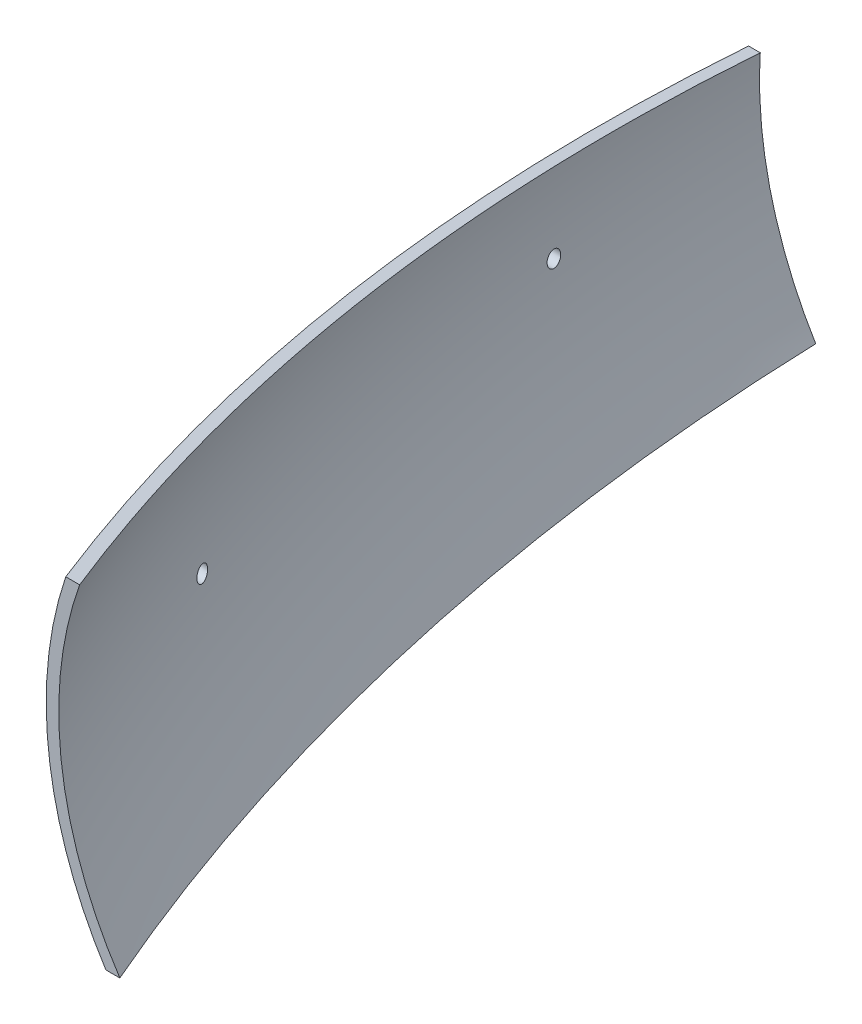
SolidWorks part; units mm, degrees
ref_plane "Front Plane" through (0, 0, 0) normal (0, 0, 1) x (1, 0, 0)
ref_plane "Top Plane" through (0, 0, 0) normal (0, 1, 0) x (1, 0, 0)
ref_plane "Right Plane" through (0, 0, 0) normal (1, 0, 0) x (0, 0, -1)
sketch "Sketch2" plane through (0, 0, 0) normal (0, 0, 1) x (1, 0, 0)
  line L0 (72.3704, 0) -> (82.3704, 0)
  line L1 (43.5787, 250) -> (53.5787, 250)
  arc A0 (72.3704, 0) -> (43.5787, 250) centre (340.9441, 157.5887) cw
  arc A1 (82.3704, 0) -> (53.5787, 250) centre (338.8585, 156.1968) cw
  dimension "D1" = 250
  dimension "D2" = 10
sketch "Shovel Curvature Axis" plane through (0, 0, 0) normal (0, 0, 1) x (1, 0, 0)
  line L0 (2000, -13.3717) -> (2000, 182.6602)
  line L1 (0, -403.9611) -> (0, 403.9611) construction
  dimension "D1" = 2000
revolve "Revolve1" add sketch "Sketch2" angle 88 about L0
sketch "Sketch5" plane through (0, 0, 0) normal (1, 0, 0) x (0, 0, -1)
  line L0 (-762.4592, 250) -> (-762.4592, 0)
  line L1 (-762.4592, 0) -> (-62.4592, 0)
  line L2 (-62.4592, 0) -> (-62.4592, 175)
  line L3 (-62.4592, 175) -> (-762.4592, 250)
  line L4 (0, 250) -> (-1945.2356, 250) construction
  line L5 (1046.9389, 0) -> (-1046.9389, 0) construction
  line L7 (-2824.2265, 1130.828) -> (2976.3022, 1130.828)
  line L8 (-2824.2265, 1130.828) -> (-2824.2265, -1305.0611)
  line L9 (-2824.2265, -1305.0611) -> (2976.3022, -1305.0611)
  line L10 (2976.3022, 1130.828) -> (2976.3022, -1305.0611)
  line L11 (-2824.2265, 1130.828) -> (2976.3022, -1305.0611) construction
  line L12 (-2824.2265, -1305.0611) -> (2976.3022, 1130.828) construction
  point P8 (76.0379, -87.1165)
  dimension "D1" = 700
  dimension "D2" = 175
extrude "Cut-Extrude2" cut sketch "Sketch5" against normal through all both and the other way through all
sketch "Sketch6" plane through (0, 0, 0) normal (1, 0, 0) x (0, 0, -1)
  line L0 (-587.4592, 130.34) -> (-237.4592, 130.34) construction
  line L1 (170.2439, 0) -> (-170.2439, 0) construction
  line L2 (-762.4592, 27.256) -> (-62.4592, 27.256) construction
  line L3 (-762.4592, 250) -> (-762.4592, 0) construction
  line L4 (-62.4592, 0) -> (-62.4592, 175) construction
  line L5 (-412.4592, 27.256) -> (-412.4592, 130.34) construction
  circle A0 centre (-587.4592, 130.34) radius 6
  circle A1 centre (-237.4592, 130.34) radius 6
  dimension "D3" = 12
  dimension "D1" = 130.34
  dimension "D2" = 350
extrude "Cut-Extrude4" cut sketch "Sketch6" along normal through all both
ref_plane "Locating Plane" through (30, 0, 0) normal (1, 0, 0) x (0, 0, -1)
equation "\"shovelWidth\" = 700"
equation "\"D1@Sketch5\"=\"shovelWidth\""
